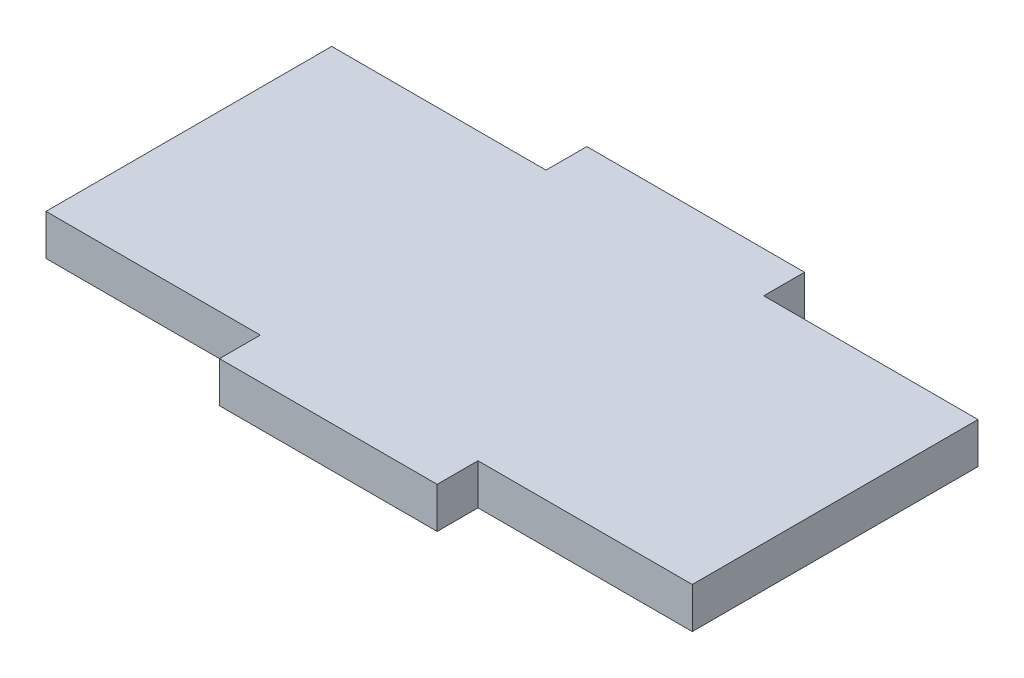
SolidWorks part; units mm, degrees
ref_plane "Alzado" through (0, 0, 0) normal (0, 0, 1) x (1, 0, 0)
ref_plane "Planta" through (0, 0, 0) normal (0, 1, 0) x (1, 0, 0)
ref_plane "Vista lateral" through (0, 0, 0) normal (1, 0, 0) x (0, 0, -1)
sketch "Croquis1" plane through (0, 0, 0) normal (0, 1, 0) x (1, 0, 0)
  line L0 (0, 3) -> (0, 24)
  line L1 (-15.75, 27) -> (-31.75, 27)
  line L2 (-31.75, 27) -> (-15.75, 27)
  line L3 (-15.75, 27) -> (-15.75, 24)
  line L4 (-15.75, 24) -> (0, 24)
  line L6 (-31.75, 24) -> (-47.5, 24)
  line L7 (-31.75, 27) -> (-31.75, 24)
  line L8 (-47.5, 3) -> (-47.5, 24)
  line L10 (-31.75, 0) -> (-31.75, 3)
  line L11 (-31.75, 3) -> (-47.5, 3)
  line L13 (-15.75, 3) -> (0, 3)
  line L14 (-15.75, 0) -> (-15.75, 3)
  line L15 (-31.75, 0) -> (-15.75, 0)
  line L16 (-15.75, 0) -> (-31.75, 0)
  dimension "D1" = 47.5
  dimension "D2" = 21
  dimension "D3" = 3
  dimension "D4" = 3
  dimension "D5" = 21
extrude "Saliente-Extruir1" add sketch "Croquis1" along normal blind 3 contours L10 L15 L14 L13 L0 L4 L3 L1 L7 L6 L8 L11
